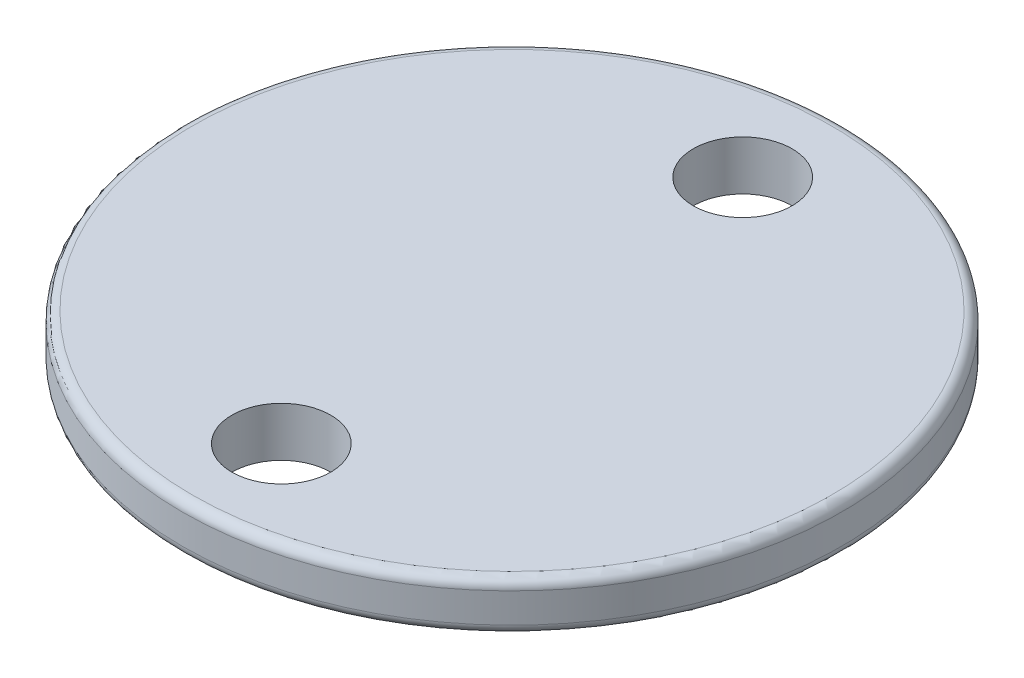
SolidWorks part; units mm, degrees
ref_plane "Front Plane" through (0, 0, 0) normal (0, 0, 1) x (1, 0, 0)
ref_plane "Top Plane" through (0, 0, 0) normal (0, 1, 0) x (1, 0, 0)
ref_plane "Right Plane" through (0, 0, 0) normal (1, 0, 0) x (0, 0, -1)
sketch "草图1" plane through (0, 0, 0) normal (0, 1, 0) x (1, 0, 0)
  circle A0 centre (0, 7) radius 1.5
  circle A1 centre (0, -7) radius 1.5
  circle A10 centre (0, 0) radius 10
extrude "凸台-拉伸1" add sketch "草图1" along normal blind 1.5
fillet "圆角1" radius 0.3 2 edges at (0, 0, 10) (0, 1.5, 10)
